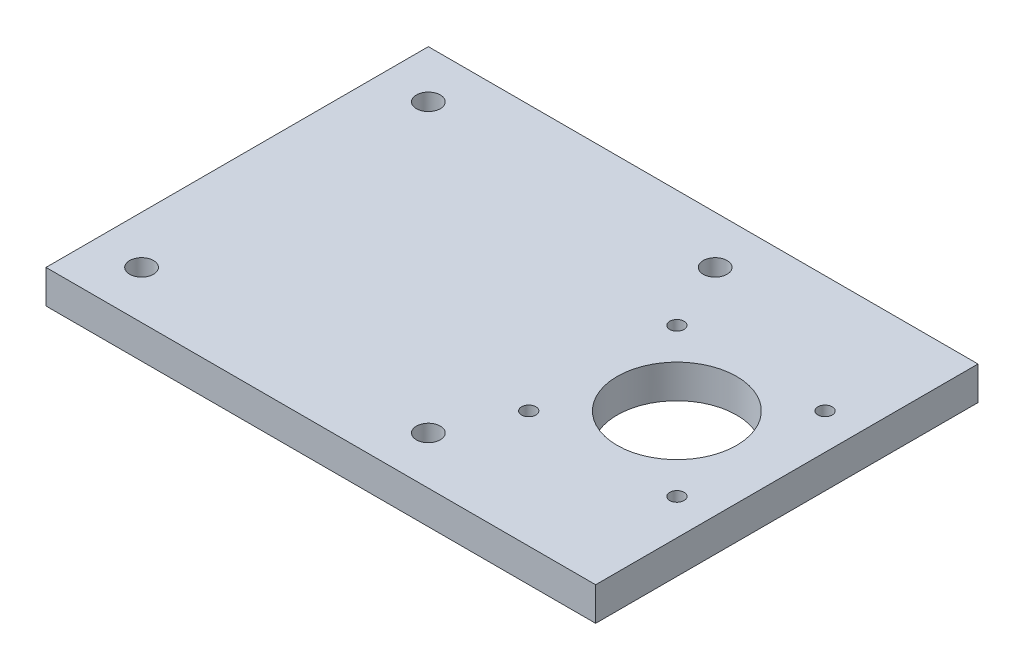
SolidWorks part; units mm, degrees
ref_plane "Front Plane" through (0, 0, 0) normal (0, 0, 1) x (1, 0, 0)
ref_plane "Top Plane" through (0, 0, 0) normal (0, 1, 0) x (1, 0, 0)
ref_plane "Right Plane" through (0, 0, 0) normal (1, 0, 0) x (0, 0, -1)
sketch "Sketch1" plane through (0, 0, 0) normal (0, 1, 0) x (1, 0, 0)
  line L2 (0, 0) -> (0, 80)
  line L12 (80, 0) -> (80, 80)
  line L14 (80, 0) -> (0, 0)
  line L15 (80, 80) -> (0, 80)
  point P0 (0, 0)
  dimension "D1" = 80
  dimension "D2" = 80
extrude "Boss-Extrude1" add sketch "Sketch1" along normal blind 7
sketch "Sketch2" plane through (0, 0, 0) normal (0, -1, 0) x (1, 0, 0)
  line L0 (40, 0) -> (40, -80) construction
  line L1 (80, 0) -> (0, 0) construction
  line L2 (80, -80) -> (0, -80) construction
  line L3 (80, -40) -> (0, -40) construction
  line L4 (30, 0) -> (50, 0) construction
  line L5 (30, 0) -> (30, -80) construction
  line L6 (30, -80) -> (50, -80) construction
  line L7 (50, 0) -> (50, -80) construction
  line L8 (30, 0) -> (50, -80) construction
  line L9 (30, -80) -> (50, 0) construction
  line L10 (10, 0) -> (70, 0) construction
  line L11 (10, 0) -> (10, -80) construction
  line L12 (10, -80) -> (70, -80) construction
  line L13 (70, 0) -> (70, -80) construction
  line L14 (10, 0) -> (70, -80) construction
  line L15 (10, -80) -> (70, 0) construction
  line L16 (80, 0) -> (80, -80) construction
  line L17 (0, 0) -> (0, -80) construction
  circle A0 centre (70, -70) radius 2.5
  circle A1 centre (70, -10) radius 2.5
  circle A2 centre (10, -10) radius 2.5
  circle A3 centre (10, -70) radius 2.5
  point P6 (40, -40)
  point P11 (40, -40)
  dimension "D7" = 5
  dimension "D8" = 5
  dimension "D9" = 5
  dimension "D10" = 5
  dimension "D1" = 20
  dimension "D2" = 60
  dimension "D3" = 30
  dimension "D4" = 60
  dimension "D5" = 30
  dimension "D6" = 60
extrude "Cut-Extrude1" cut sketch "Sketch2" against normal blind 10
sketch "Sketch4" plane through (80, 0, 0) normal (1, 0, 0) x (0, 0, -1)
  line L1 (0, 0) -> (80, 0)
  line L2 (0, 0) -> (0, 7)
  line L3 (0, 7) -> (80, 7)
  line L4 (80, 0) -> (80, 7)
extrude "Boss-Extrude2" add sketch "Sketch4" along normal blind 35
sketch "Sketch3" plane through (0, 0, 0) normal (0, -1, 0) x (1, 0, 0)
  line L0 (0, -40) -> (70, -40) construction
  line L1 (0, 0) -> (0, -80) construction
  line L2 (70, -10) -> (70, -70) construction
  line L4 (114, -18) -> (70, -18) construction
  line L5 (114, -18) -> (114, -62) construction
  line L6 (114, -62) -> (70, -62) construction
  line L7 (70, -18) -> (70, -62) construction
  line L8 (76.5, -24.5) -> (107.5, -24.5) construction
  line L9 (76.5, -24.5) -> (76.5, -55.5) construction
  line L14 (76.5, -55.5) -> (107.5, -55.5) construction
  line L15 (107.5, -24.5) -> (107.5, -55.5) construction
  line L20 (76.5, -24.5) -> (107.5, -55.5) construction
  line L21 (76.5, -55.5) -> (107.5, -24.5) construction
  circle A4 centre (107.5, -24.5) radius 1.5
  circle A5 centre (107.5, -55.5) radius 1.5
  circle A6 centre (76.5, -55.5) radius 1.5
  circle A7 centre (76.5, -24.5) radius 1.5
  circle A8 centre (92, -40) radius 12.5
  point P8 (92, -40)
  point P14 (92, -40)
  point P21 (82, -40)
  dimension "D5" = 3
  dimension "D6" = 3
  dimension "D7" = 3
  dimension "D8" = 3
  dimension "D9" = 25
  dimension "D1" = 44
  dimension "D2" = 44
  dimension "D3" = 31
  dimension "D4" = 31
  dimension "D10" = 22
  dimension "D11" = 22
extrude "Cut-Extrude2" cut sketch "Sketch3" against normal blind 10
